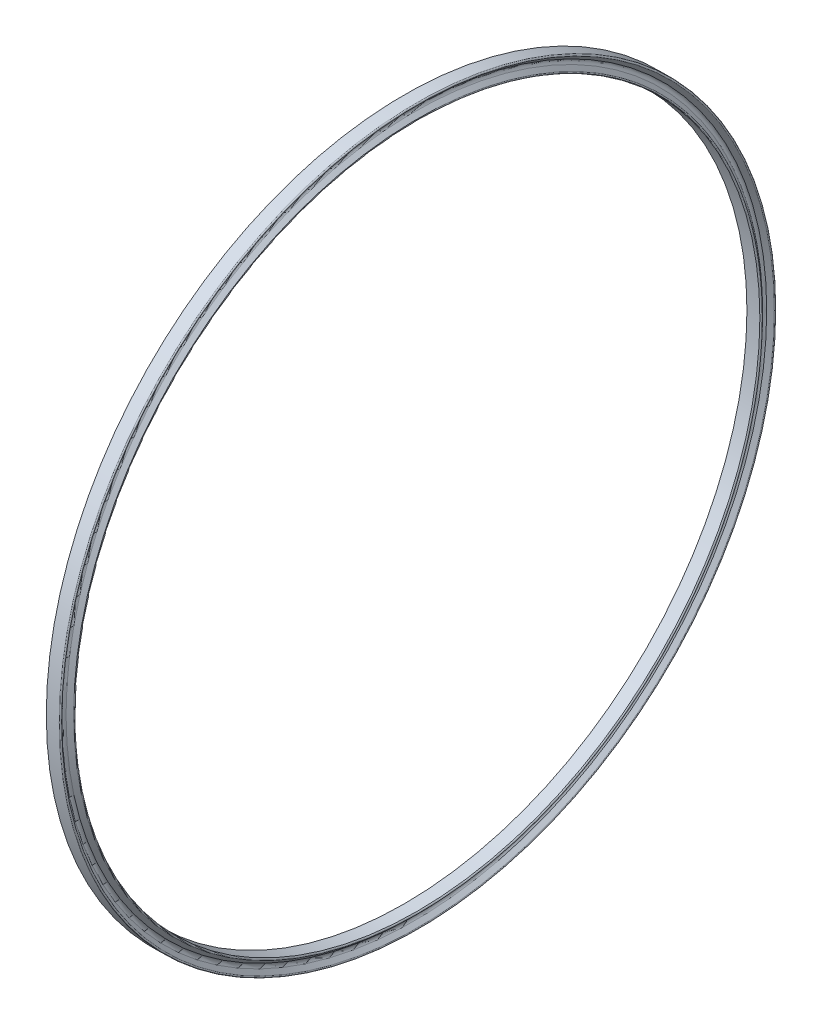
SolidWorks part; units mm, degrees
material "PP Copolymer"
ref_plane "Ön Düzlem" through (0, 0, 0) normal (0, 0, 1) x (1, 0, 0)
ref_plane "Üst Düzlem" through (0, 0, 0) normal (0, 1, 0) x (1, 0, 0)
ref_plane "Sağ Düzlem" through (0, 0, 0) normal (1, 0, 0) x (0, 0, -1)
sketch "Sketch1" plane through (0, 0, 0) normal (0, 0, 1) x (1, 0, 0)
  line L0 (-75.5758, 0) -> (75.3029, 0) construction
  line L1 (26.0589, -34.08) -> (29.845, -34.08) construction
  line L2 (27.3175, -33.33) -> (26.0589, -33.33)
  line L3 (27.3882, -33.5007) -> (27.021, -33.8679)
  line L4 (27.3175, -34.83) -> (26.0589, -34.83)
  line L5 (26.0589, -34.83) -> (26.0589, -33.33)
  line L6 (27.021, -34.2921) -> (27.3882, -34.6593)
  arc A0 (27.021, -33.8679) -> (27.021, -34.2921) centre (27.2332, -34.08) ccw
  arc A1 (27.3175, -34.83) -> (27.3882, -34.6593) centre (27.3175, -34.73) ccw
  arc A2 (27.3882, -33.5007) -> (27.3175, -33.33) centre (27.3175, -33.43) ccw
  point P10 (26.8089, -34.08)
  point P13 (27.5589, -34.83)
  dimension "D1" = 1.5
  dimension "D2" = 0.3
  dimension "D6" = 0.1
  dimension "D3" = 34.83
  dimension "D4" = 33.33
  dimension "D5" = 1.5
revolve "Revolve1" add sketch "Sketch1" angle 360 about L0
